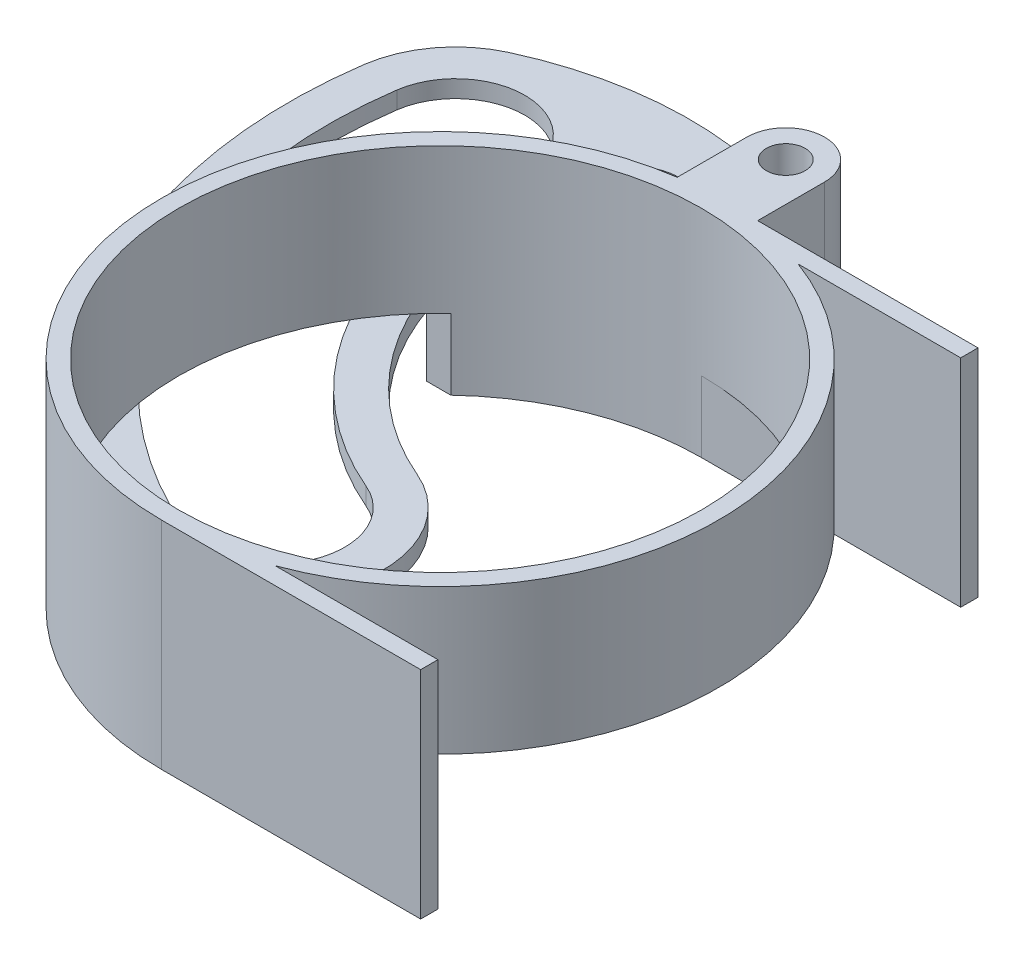
SolidWorks part; units mm, degrees
ref_plane "Front Plane" through (0, 0, 0) normal (0, 0, 1) x (1, 0, 0)
ref_plane "Top Plane" through (0, 0, 0) normal (0, 1, 0) x (1, 0, 0)
ref_plane "Right Plane" through (0, 0, 0) normal (1, 0, 0) x (0, 0, -1)
sketch "Sketch1" plane through (0, 0, 0) normal (0, 1, 0) x (1, 0, 0)
  circle A0 centre (0, 0) radius 30.25
  circle A1 centre (0, 0) radius 32.25
  dimension "D1" = 2
  dimension "D2" = 60.5
extrude "Boss-Extrude1" add sketch "Sketch1" along normal blind 25
sketch "Sketch2" plane through (0, 0, 0) normal (0, 1, 0) x (1, 0, 0)
  line L0 (0, -12) -> (0, -30.25)
  line L1 (0, 30.25) -> (38.6387, 30.25)
  line L2 (0, 30.25) -> (0, 22)
  line L3 (0, -30.25) -> (38.6387, -30.25)
  line L4 (38.6387, 30.25) -> (38.6387, -30.25)
  line L5 (0, -12) -> (-36.2042, -12)
  line L7 (0, 22) -> (-36.2042, 22)
  line L8 (-36.2042, -12) -> (-36.2042, 22)
  line L9 (0, 22) -> (0, -12) construction
  circle A0 centre (0, 0) radius 30.25 construction
  dimension "D1" = 22
  dimension "D2" = 12
extrude "Cut-Extrude1" cut sketch "Sketch2" along normal blind 8.2
sketch "Sketch3" plane through (0, 0, 0) normal (0, 1, 0) x (1, 0, 0)
  line L0 (0, 0) -> (0, 40) construction
  line L1 (-44.5501, 46.3475) -> (0, 40) construction
  line L4 (-17.6616, -1.3892) -> (0, 40) construction
  line L5 (0, 0) -> (0, -5) construction
  arc A2 (-17.6616, -1.3892) -> (-44.5501, 46.3475) centre (0, 40) cw construction
  arc A3 (-56.9251, 48.1107) -> (-22.5676, -12.8862) centre (0, 40) ccw
  arc A4 (-32.1751, 44.5843) -> (-12.7556, 10.1078) centre (0, 40) ccw
  arc A5 (-32.1751, 44.5843) -> (-35.8498, 55.3228) centre (-44.5501, 46.3475) ccw
  arc A6 (-22.5676, -12.8862) -> (-12.7556, 10.1078) centre (-17.6616, -1.3892) ccw
  arc A7 (-49.7915, 57.6955) -> (-56.9251, 48.1107) centre (-44.5501, 46.3475) ccw
  arc A8 (-17.6616, -1.3892) -> (-44.5501, 46.3475) centre (0, 40) cw construction
  arc A9 (-52.4701, 47.476) -> (-20.8015, -8.7473) centre (0, 40) ccw
  arc A10 (-36.6301, 45.2191) -> (-14.5218, 5.9689) centre (0, 40) ccw
  arc A11 (-36.6301, 45.2191) -> (-52.4701, 47.476) centre (-44.5501, 46.3475) ccw
  arc A12 (-20.8015, -8.7473) -> (-14.5218, 5.9689) centre (-17.6616, -1.3892) ccw
  arc A13 (0, 40) -> (-37.4488, 58.1634) centre (-32.5996, 20.474) ccw construction
  arc A14 (2.5737, 41.5415) -> (-49.7915, 57.6955) centre (-32.5996, 20.474) ccw
  arc A15 (-2.5737, 38.4585) -> (-35.8498, 55.3228) centre (-32.5996, 20.474) ccw
  arc A16 (-2.5737, 38.4585) -> (2.5737, 41.5415) centre (0, 40) ccw
  point P0 (0, 40)
  point P2 (-39.2081, 17.9155)
  point P4 (-15.9749, 54.2844)
  point P5 (0, 0)
  point P8 (0, 0)
  point P13 (-36.7687, 7.6107)
  point P24 (0, 0)
  point P28 (0, 0)
  point P29 (-44.6737, 45.4094)
  point P30 (0, 0)
  point P31 (-37.3737, 60.7694)
  point P33 (0, 0)
  point P34 (0, 0)
  point P35 (0, 0)
  point P36 (0, 0)
  point P37 (0, 0)
  point P38 (0, 0)
  point P39 (0, 0)
  point P40 (0, 0)
  point P41 (0, 0)
  dimension "D2" = 25
  dimension "D3" = 5
  dimension "D6" = 12.5
  dimension "D8" = 8
  dimension "D5" = 6
  dimension "D9" = 35
  dimension "D1" = 75
  dimension "D4" = 40
extrude "Boss-Extrude2" add sketch "Sketch3" along normal blind 2 separate body
fillet "Fillet1" radius 5 1 edges at (-35.8498, 1, -55.3228)
sketch "Sketch4" plane through (0, 2, 0) normal (0, 1, 0) x (1, 0, 0)
  circle A0 centre (0, 40) radius 2
  arc A2 (-2.5737, 38.4585) -> (2.5737, 41.5415) centre (0, 40) ccw construction
  dimension "D1" = 4
extrude "Boss-Extrude3" add sketch "Sketch4" along normal blind 15
chamfer "Chamfer1" distance 1 angle 45 1 edges at (0, 17, -38)
sketch "Sketch5" plane through (0, 25, 0) normal (0, 1, 0) x (1, 0, 0)
  line L0 (-4.5, 40) -> (-4.5, 31.9345)
  line L1 (4.5, 40) -> (4.5, 31.9345)
  circle A0 centre (0, 40) radius 2.25
  circle A1 centre (0, 0) radius 32.25 construction
  arc A3 (4.5, 40) -> (-4.5, 40) centre (0, 40) ccw
  arc A4 (4.5, 31.9345) -> (-4.5, 31.9345) centre (0, 0) ccw
  circle A6 centre (0, 40) radius 2 construction
  dimension "D1" = 4.5
  dimension "D2" = 9
extrude "Boss-Extrude4" add sketch "Sketch5" against normal offset from surface (22.6 mm away) 0.4 up to face at (0, 2, -38)
sketch "Sketch6" plane through (0, 0, 0) normal (0, -1, 0) x (1, 0, 0)
  line L1 (0, -30.25) -> (30, -30.25)
  line L2 (0, -30.25) -> (0, -32.25)
  line L3 (0, -32.25) -> (30, -32.25)
  line L4 (30, -30.25) -> (30, -32.25)
  arc A0 (-23.581, -22) -> (11.1803, -30.25) centre (0, 0) ccw construction
  dimension "D1" = 30
extrude "Boss-Extrude5" add sketch "Sketch6" against normal up to surface (25 mm away)
mirror "Mirror1" about plane through (0, 0, 0) normal (0, 0, 1) of "Boss-Extrude5"
